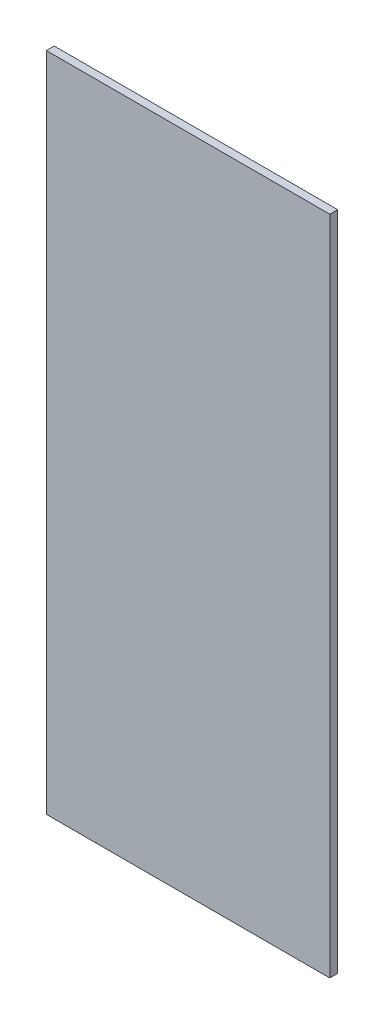
SolidWorks part; units mm, degrees
ref_plane "Plan de face" through (0, 0, 0) normal (0, 0, 1) x (1, 0, 0)
ref_plane "Plan de dessus" through (0, 0, 0) normal (0, 1, 0) x (1, 0, 0)
ref_plane "Plan de droite" through (0, 0, 0) normal (1, 0, 0) x (0, 0, -1)
sketch "Esquisse1" plane through (0, 0, 0) normal (0, 0, 1) x (1, 0, 0)
  line L1 (-90, 210) -> (90, 210)
  line L2 (-90, 210) -> (-90, -210)
  line L3 (-90, -210) -> (90, -210)
  line L4 (90, 210) -> (90, -210)
  line L5 (-90, 210) -> (90, -210) construction
  line L6 (-90, -210) -> (90, 210) construction
  point P0 (0, 0)
  dimension "D1" = 180
  dimension "D2" = 420
extrude "Boss.-Extru.1" add sketch "Esquisse1" along normal blind 5
